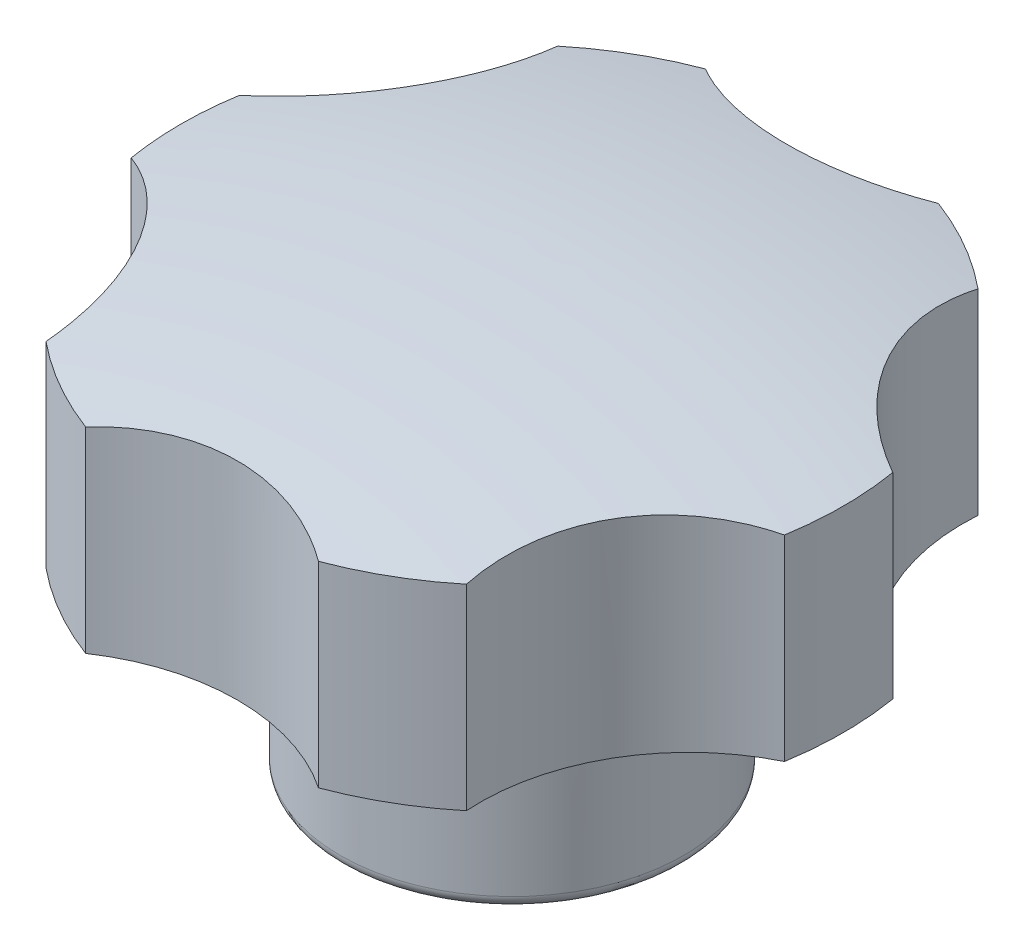
SolidWorks part; units mm, degrees
ref_plane "Front" through (0, 0, 0) normal (0, 0, 1) x (1, 0, 0)
ref_plane "Top" through (0, 0, 0) normal (0, 1, 0) x (1, 0, 0)
ref_plane "Right" through (0, 0, 0) normal (1, 0, 0) x (0, 0, -1)
sketch "草图1" plane through (0, 0, 0) normal (0, 0, 1) x (1, 0, 0)
  line L0 (0, 0) -> (-14, 0)
  line L1 (-14, 0) -> (-14, 16.1652)
  line L2 (-14, 16.1652) -> (-27, 16.1652)
  line L3 (-27, 16.1652) -> (-27, 32.1652)
  line L4 (0, 0) -> (0, 35)
  arc A1 (-27, 32.1652) -> (0, 35) centre (0, -95) cw
  point P3 (0, 0)
  point P8 (-39.2438, 28.9352)
  dimension "D2" = 35
  dimension "D5" = 27
  dimension "D3" = 130
  dimension "D1" = 14
  dimension "D4" = 16
revolve "旋转1" add sketch "草图1" angle 360 about L4
sketch "草图2" plane through (0, 16.1652, 0) normal (0, -1, 0) x (1, 0, 0)
  line L0 (0, 0) -> (36.428, 0) construction
  line L1 (0, 0) -> (0, 34.4034) construction
  arc A1 (-9.4954, 25.2752) -> (9.4954, 25.2752) centre (0, 39.3762) ccw
  arc A2 (17.1413, 20.8609) -> (26.6367, 4.4144) centre (34.1008, 19.6881) ccw
  arc A3 (26.6367, -4.4144) -> (17.1413, -20.8609) centre (34.1008, -19.6881) ccw
  arc A4 (9.4954, -25.2752) -> (-9.4954, -25.2752) centre (0, -39.3762) ccw
  arc A5 (-17.1413, -20.8609) -> (-26.6367, -4.4144) centre (-34.1008, -19.6881) ccw
  arc A6 (-26.6367, 4.4144) -> (-17.1413, 20.8609) centre (-34.1008, 19.6881) ccw
  circle A8 centre (0, 0) radius 27
  circle A9 centre (0, 0) radius 27
  circle M9 centre (0, 0) radius 27
  dimension "D1" = 34
  dimension "D2" = 6
  dimension "D3" = 0
extrude "切除-拉伸1" cut sketch "草图2" against normal through all contours A6 M9 | A1 M9 | A2 M9 | A3 M9 | A4 M9 | A5 M9
hole_wizard "Ø10.0 (10) 直径孔1" positions "草图3" profile "草图4" hole size "Ø10.0" standard "GB"
sketch "草图3" plane through (0, 0, 0) normal (0, -1, 0) x (-1, 0, 0)
  point P0 (0, 0)
sketch "草图4" plane through (0, 0, 0) normal (1, 0, 0) x (0, 0, -1)
  line L0 (0, 0) -> (0, 20)
  line L1 (0, 20) -> (5, 16.9957)
  line L2 (5, 16.9957) -> (5, 0)
  line L5 (5, 0) -> (0, 0)
  line L10 (0, 20) -> (-5, 16.9957) construction
  line L11 (0, -6.35) -> (0, 107.95) construction
  dimension "孔直径" = 10
  dimension "孔深度" = 20
  dimension "导头角度" = 118
fillet "圆角1" radius 1 1 edges at (0, 0, -14)
